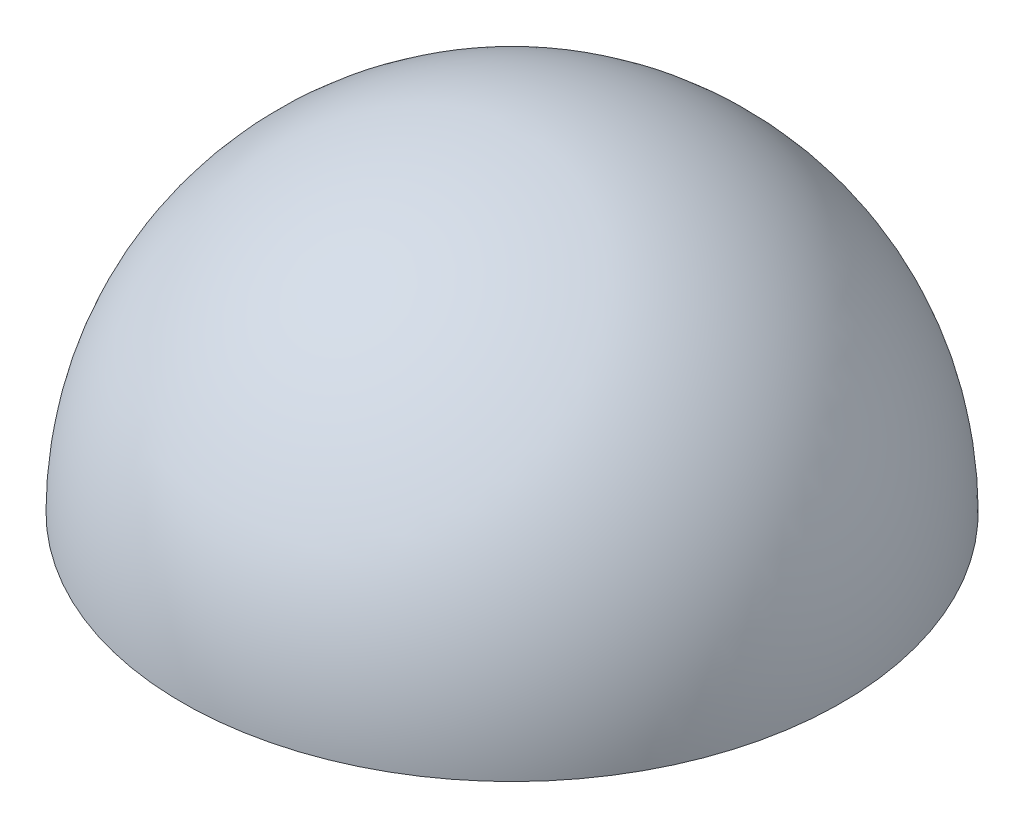
SolidWorks part; units mm, degrees
ref_plane "Front Plane" through (0, 0, 0) normal (0, 0, 1) x (1, 0, 0)
ref_plane "Top Plane" through (0, 0, 0) normal (0, 1, 0) x (1, 0, 0)
ref_plane "Right Plane" through (0, 0, 0) normal (1, 0, 0) x (0, 0, -1)
sketch "Sketch2" plane through (0, 0, 0) normal (-1, 0, 0) x (0, 1, 0)
  line L0 (0, 0) -> (0, 45)
  line L1 (0, 0) -> (45, 0)
  arc A1 (0, 45) -> (45, 0) centre (0, 0) cw
  dimension "D1" = 45
  dimension "D2" = 45
revolve "Revolve1" add sketch "Sketch2" angle 360 about L1
